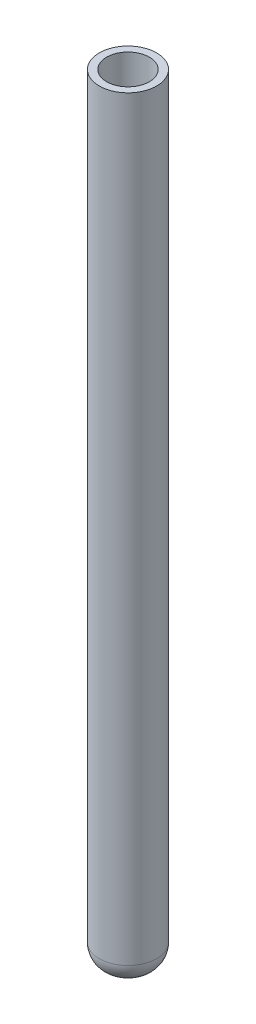
SolidWorks part; units mm, degrees
material "Nickel silver 65-12, UNS C75700"
ref_plane "Front" through (0, 0, 0) normal (0, 0, 1) x (1, 0, 0)
ref_plane "Top" through (0, 0, 0) normal (0, 1, 0) x (1, 0, 0)
ref_plane "Right" through (0, 0, 0) normal (1, 0, 0) x (0, 0, -1)
sketch "Sketch1" plane through (0, 0, 0) normal (1, 0, 0) x (0, 0, -1)
  line L0 (0.51, 0) -> (0.51, -10)
  line L1 (0.51, -10) -> (0, -10)
  line L2 (0, -10) -> (0, -18.54)
  line L3 (0, -18.54) -> (0.685, -18.54)
  line L8 (0.685, -18.54) -> (0.685, 0)
  line L11 (0.685, 0) -> (0.51, 0)
  dimension "D4" = 0.51
  dimension "D9" = 10
  dimension "D2" = 18.54
  dimension "D1" = 0.685
revolve "Revolve1" add sketch "Sketch1" angle 360 about L2
fillet "Fillet1" radius 0.5 1 edges at (0, -18.54, 0.685)
equation "\"D4@Sketch1\"=1.02/2"
equation "\"D1@Sketch1\"=1.37/2"
equation "\"D2@Sketch1\"=24.64-6.1"
